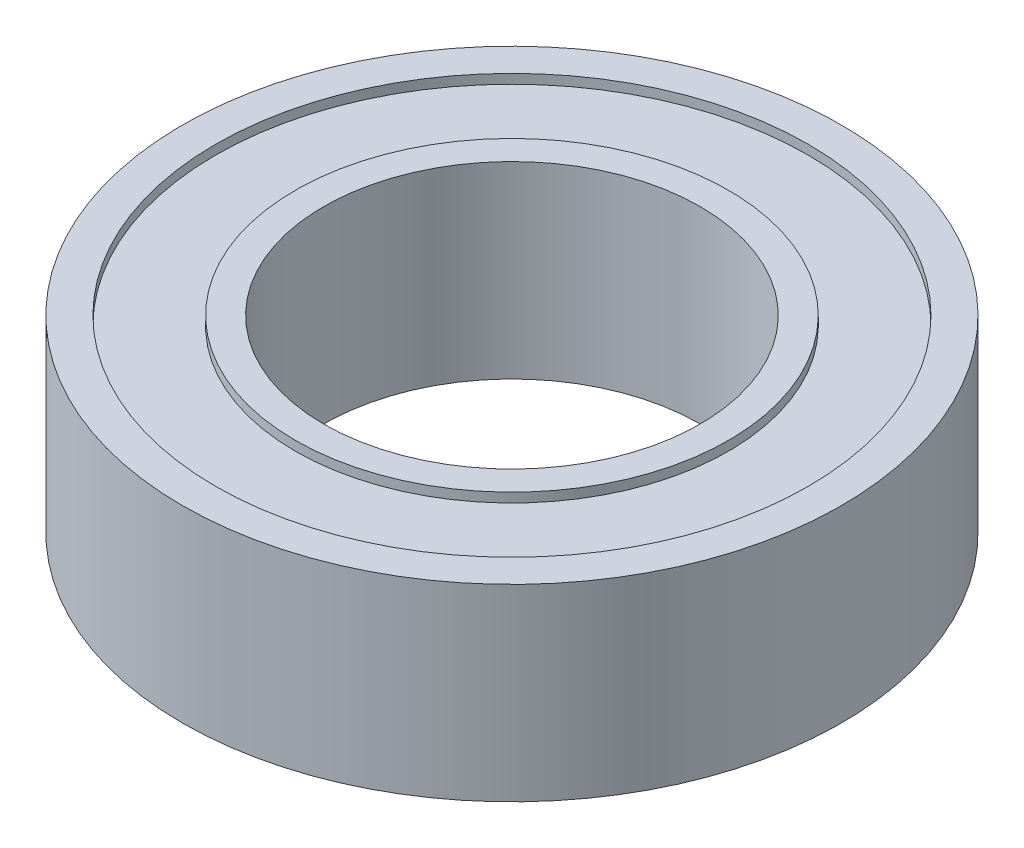
SolidWorks part; units mm, degrees
ref_plane "前视基准面" through (0, 0, 0) normal (0, 0, 1) x (1, 0, 0)
ref_plane "上视基准面" through (0, 0, 0) normal (0, 1, 0) x (1, 0, 0)
ref_plane "右视基准面" through (0, 0, 0) normal (1, 0, 0) x (0, 0, -1)
other "Configuration Table"
sketch "草图1" plane through (0, 0, 0) normal (0, 1, 0) x (1, 0, 0)
  circle A0 centre (0, 0) radius 3.5
  circle A1 centre (0, 0) radius 2
extrude "凸台-拉伸1" add sketch "草图1" along normal mid plane 2
sketch "草图2" plane through (0, 1, 0) normal (0, 1, 0) x (1, 0, 0)
  circle A0 centre (0, 0) radius 3.1469
  circle A1 centre (0, 0) radius 2.3004
extrude "切除-拉伸1" cut sketch "草图2" against normal blind 0.1
mirror "镜向1" about plane through (0, 0, 0) normal (0, 1, 0) of "切除-拉伸1"
